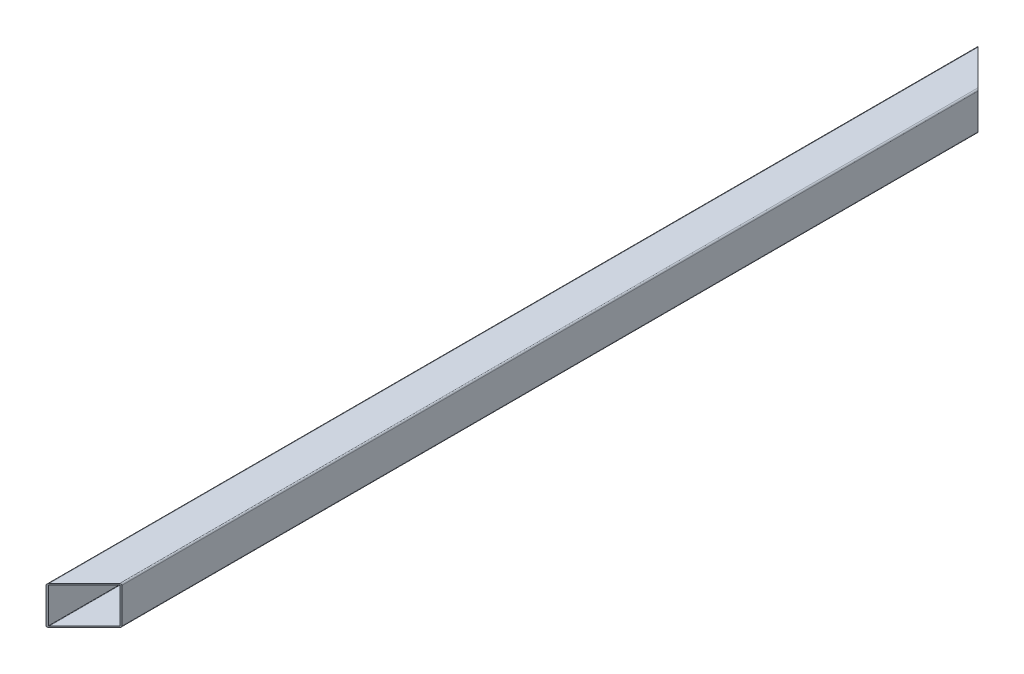
SolidWorks part; units mm, degrees
material "AISI 1020 Steel, Cold Rolled"
ref_plane "Front Plane" through (0, 0, 0) normal (0, 0, 1) x (1, 0, 0)
ref_plane "Top Plane" through (0, 0, 0) normal (0, 1, 0) x (1, 0, 0)
ref_plane "Right Plane" through (0, 0, 0) normal (1, 0, 0) x (0, 0, -1)
sketch "Sketch1" plane through (0, 0, 0) normal (0, 1, 0) x (1, 0, 0)
  line L0 (0, 0) -> (0, 980)
  dimension "D1" = 980
other "Structural Member1"
ref_plane "Plane1" through (0, 0, 0) normal (0, 0, -1) x (-1, 0, 0)
sketch "Sketch12" plane through (0, 0, 0) normal (0, 0, -1) x (-1, 0, 0)
  line L0 (-18.5, -18.8) -> (18.5, -18.8)
  line L1 (-18.8, -18.5) -> (-18.8, 18.5)
  line L2 (18.5, 18.8) -> (-18.5, 18.8)
  line L3 (18.8, 18.5) -> (18.8, -18.5)
  line L4 (-18.5, -20) -> (18.5, -20)
  line L5 (-20, -18.5) -> (-20, 18.5)
  line L6 (18.5, 20) -> (-18.5, 20)
  line L7 (20, 18.5) -> (20, -18.5)
  arc A0 (20, 18.5) -> (18.5, 20) centre (18.5, 18.5) ccw
  arc A1 (18.5, -20) -> (20, -18.5) centre (18.5, -18.5) ccw
  arc A2 (-20, -18.5) -> (-18.5, -20) centre (-18.5, -18.5) ccw
  arc A3 (-18.5, 20) -> (-20, 18.5) centre (-18.5, 18.5) ccw
  arc A4 (-18.5, 18.8) -> (-18.8, 18.5) centre (-18.5, 18.5) ccw
  arc A5 (18.8, 18.5) -> (18.5, 18.8) centre (18.5, 18.5) ccw
  arc A6 (18.5, -18.8) -> (18.8, -18.5) centre (18.5, -18.5) ccw
  arc A7 (-18.8, -18.5) -> (-18.5, -18.8) centre (-18.5, -18.5) ccw
  point P0 (-20, 0)
  point P1 (20, 0)
  point P2 (0, 20)
  point P3 (0, -20)
  point P4 (0, 0)
  point P5 (-20, -20)
  point P6 (20, -20)
  point P7 (20, 20)
  point P8 (-20, 20)
  point P33 (0, 0)
  dimension "D1" = 1.5
  dimension "Thickness" = 1.2
  dimension "V_leg" = 40
sketch "Sketch13" plane through (0, 20, 0) normal (0, 1, 0) x (1, 0, 0)
  line L0 (-20, 980) -> (33.3908, 926.6092)
  line L1 (-20, 980) -> (46.7361, 1004.4)
  line L2 (46.7361, 1004.4) -> (33.3908, 926.6092)
  line L3 (-18.5, 490) -> (18.5, 490) construction
  line L4 (-18.5, 980) -> (-18.5, 0) construction
  line L5 (18.5, 980) -> (18.5, 0) construction
  line L6 (46.7361, -24.4) -> (33.3908, 53.3908)
  line L7 (-20, 0) -> (46.7361, -24.4)
  line L8 (-20, 0) -> (33.3908, 53.3908)
extrude "Cut-Extrude1" cut sketch "Sketch13" against normal blind 50
